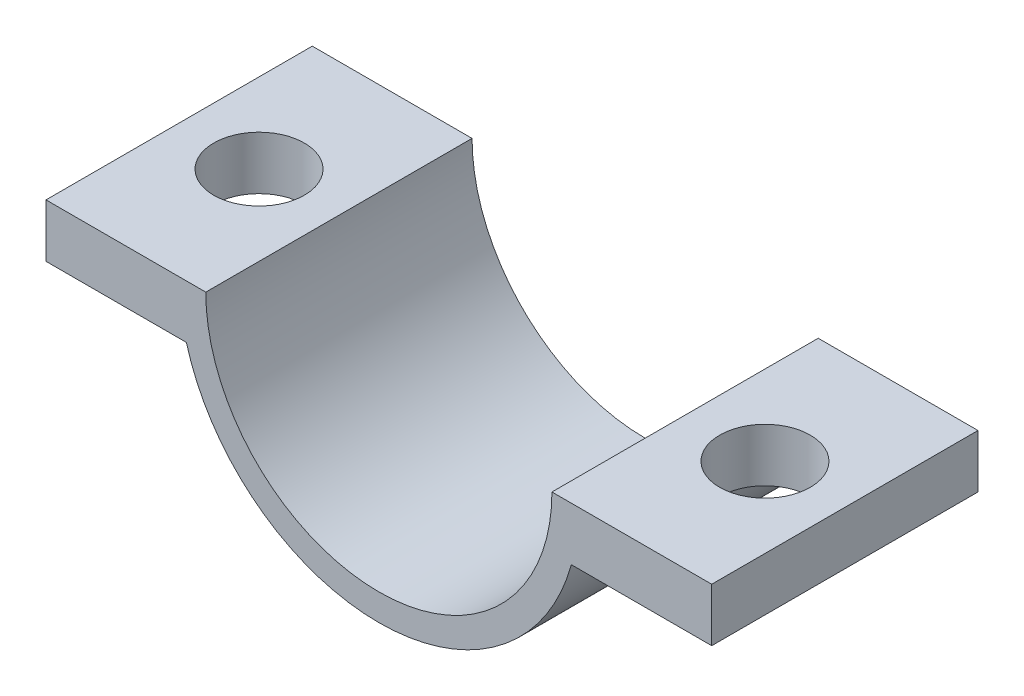
SolidWorks part; units mm, degrees
ref_plane "前视基准面" through (0, 0, 0) normal (0, 0, 1) x (1, 0, 0)
ref_plane "上视基准面" through (0, 0, 0) normal (0, 1, 0) x (1, 0, 0)
ref_plane "右视基准面" through (0, 0, 0) normal (1, 0, 0) x (0, 0, -1)
other "Configuration Table"
sketch "草图1" plane through (0, 0, 0) normal (0, 0, 1) x (1, 0, 0)
  line L0 (0, 0) -> (0, 27.602) construction
  line L3 (-27.7108, 0) -> (18.3452, 0) construction
  line L4 (-6.5, 0) -> (-12.5, 0)
  line L5 (-12.5, 0) -> (-12.5, -2)
  line L6 (-12.5, -2) -> (-7.2284, -2)
  line L7 (27.7108, 0) -> (-18.3452, 0) construction
  line L8 (12.5, -2) -> (7.2284, -2)
  line L9 (12.5, 0) -> (12.5, -2)
  line L10 (6.5, 0) -> (12.5, 0)
  arc A0 (-6.5, 0) -> (6.5, 0) centre (0, 0) ccw
  arc A1 (-7.2284, -2) -> (-0.0322, -7.4999) centre (0, 0) ccw
  arc A2 (7.2284, -2) -> (-0.0322, -7.4999) centre (0, 0) cw
  point P3 (0, 2.2338)
  point P12 (-5, 12.2712)
  point P15 (-5.4763, 19.0401)
  point P18 (6.5, 11.5292)
  point P21 (0, 0)
  dimension "D2" = 1
  dimension "D3" = 6.5
  dimension "D4" = 2
  dimension "D6" = 25
extrude "凸台-拉伸1" add sketch "草图1" along normal blind 10
sketch "草图2" plane through (0, 0, 0) normal (0, 1, 0) x (1, 0, 0)
  line L0 (-9.5, 0) -> (-9.5, -13.6469) construction
  line L1 (-6.5, 0) -> (-12.5, 0) construction
  line L2 (9.5, 0) -> (9.5, -14.2938) construction
  line L3 (12.5, 0) -> (6.5, 0) construction
  line L4 (-12.5, -5) -> (14.5768, -5) construction
  line L5 (-12.5, -10) -> (-12.5, 0) construction
  circle A0 centre (-9.5, -5) radius 1.7
  circle A1 centre (9.5, -5) radius 1.7
  point P16 (-9.5, -5)
  point P17 (9.5, -5)
  dimension "D1" = 3.4
  dimension "D2" = 3.4
extrude "切除-拉伸1" cut sketch "草图2" against normal blind 10
